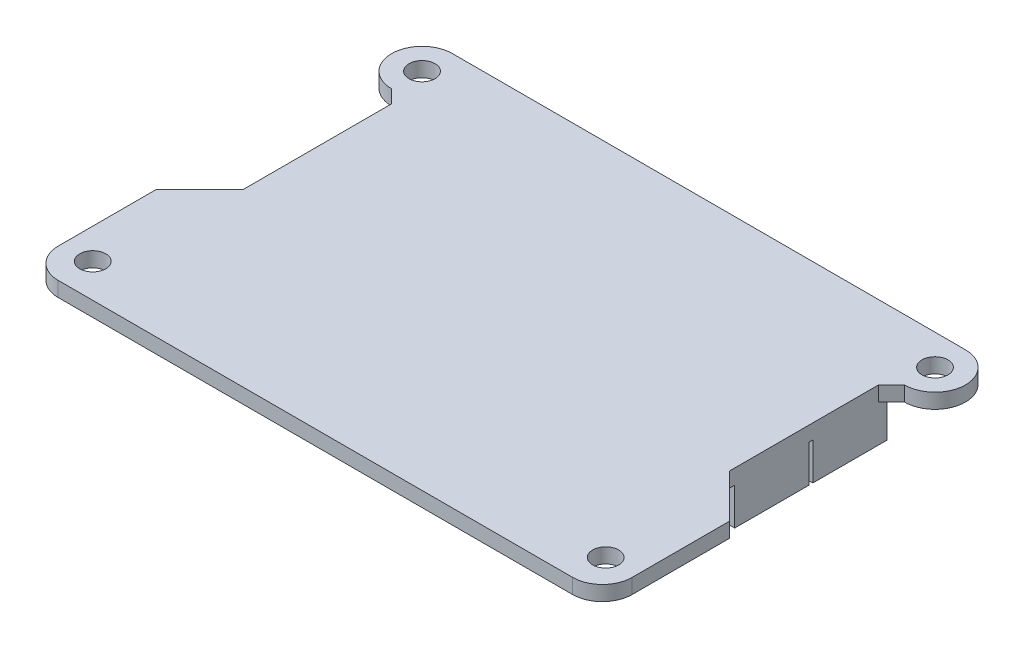
SolidWorks part; units mm, degrees
ref_plane "前视基准面" through (0, 0, 0) normal (0, 0, 1) x (1, 0, 0)
ref_plane "上视基准面" through (0, 0, 0) normal (0, 1, 0) x (1, 0, 0)
ref_plane "右视基准面" through (0, 0, 0) normal (1, 0, 0) x (0, 0, -1)
sketch "草图1" plane through (0, 0, 0) normal (0, 1, 0) x (1, 0, 0)
  line L0 (0, 0) -> (62.6522, 0) construction
  line L1 (0, 0) -> (0, 53.0134) construction
  line L2 (-34.475, 43.1409) -> (34.475, 43.1409)
  line L3 (34.475, 34.9509) -> (32.725, 33.2009)
  line L4 (32.725, 33.2009) -> (32.725, 13.2009)
  line L5 (32.725, 13.2009) -> (38.57, 7.3559)
  line L6 (38.57, 7.3559) -> (38.57, -9.7591)
  line L7 (38.57, -9.7591) -> (-38.57, -9.7591)
  line L8 (-38.57, 7.3559) -> (-38.57, -9.7591)
  line L9 (-32.725, 13.2009) -> (-38.57, 7.3559)
  line L10 (-32.725, 33.2009) -> (-32.725, 13.2009)
  line L11 (-34.475, 34.9509) -> (-32.725, 33.2009)
  arc A0 (34.475, 34.9509) -> (34.475, 43.1409) centre (34.475, 39.0459) ccw
  circle A1 centre (34.475, 39.0459) radius 1.75
  circle A2 centre (34.475, -5.2141) radius 1.75
  circle A3 centre (-34.475, -5.2141) radius 1.75
  circle A4 centre (-34.475, 39.0459) radius 1.75
  arc A5 (-34.475, 34.9509) -> (-34.475, 43.1409) centre (-34.475, 39.0459) cw
  point P23 (0, -9.7591)
  point P26 (0, 43.1409)
  dimension "D5" = 3.5
  dimension "D6" = 135
  dimension "D1" = 68.95
  dimension "D2" = 44.26
  dimension "D3" = 52.9
  dimension "D4" = 77.14
  dimension "D7" = 20
  dimension "D8" = 135
extrude "凸台-拉伸1" add sketch "草图1" along normal blind 2
fillet "圆角1" radius 4 2 edges at (-38.57, 1, 9.7591) (38.57, 1, 9.7591)
sketch "草图2" plane through (0, 0, 0) normal (0, -1, 0) x (1, 0, 0)
  line L0 (32.725, -13.2009) -> (32.725, -33.2009) construction
  line L1 (32.725, -34.3689) -> (27.725, -34.3689)
  line L2 (32.725, -34.3689) -> (32.725, -24.3689)
  line L3 (32.725, -24.3689) -> (27.725, -24.3689)
  line L4 (27.725, -34.3689) -> (27.725, -24.3689)
  line L5 (-27.725, -32.8455) -> (-32.725, -32.8455)
  line L6 (32.725, -23.8774) -> (27.725, -23.8774)
  line L7 (32.725, -23.8774) -> (32.725, -13.8774)
  line L8 (32.725, -13.8774) -> (27.725, -13.8774)
  line L9 (27.725, -23.8774) -> (27.725, -13.8774)
  line L10 (-27.725, -32.8455) -> (-27.725, -22.8455)
  line L11 (-27.725, -22.8455) -> (-32.725, -22.8455)
  line L12 (-32.725, -32.8455) -> (-32.725, -22.8455)
  line L13 (-32.725, -33.2009) -> (-32.725, -13.2009) construction
  dimension "D1" = 5
  dimension "D2" = 10
  dimension "D3" = 5
  dimension "D4" = 10
  dimension "D5" = 5
  dimension "D6" = 10
extrude "凸台-拉伸2" add sketch "草图2" along normal blind 5
sketch "草图4" plane through (0, -5, 0) normal (0, -1, 0) x (1, 0, 0)
  line L0 (31.631, -19.9862) -> (31.631, -17.9323)
  line L1 (31.631, -17.9323) -> (31.131, -17.9323)
  line L2 (31.131, -17.9323) -> (31.131, -18.6563)
  line L3 (31.131, -18.6563) -> (29.131, -18.6563)
  line L4 (29.131, -18.6563) -> (29.131, -17.9323)
  line L5 (29.131, -17.9323) -> (28.631, -17.9323)
  line L6 (28.631, -17.9323) -> (28.631, -19.9862)
  line L7 (28.631, -19.9862) -> (29.131, -19.9862)
  line L8 (29.131, -19.9862) -> (29.131, -19.152)
  line L9 (29.131, -19.152) -> (31.131, -19.152)
  line L10 (31.131, -19.152) -> (31.131, -19.9862)
  line L11 (31.131, -19.9862) -> (31.631, -19.9862)
  dimension "D1" = 3
  dimension "D2" = 0.5
  dimension "D3" = 0.5
  dimension "D4" = 0.4957
extrude "切除-拉伸1" cut sketch "草图4" against normal blind 0.2
sketch "草图5" plane through (0, 0, 0) normal (0, -1, 0) x (1, 0, 0)
  line L1 (-12.9615, -6.2539) -> (-31.138, -6.2539)
  line L2 (-12.9615, -6.2539) -> (-12.9615, 2.4297)
  line L3 (-12.9615, 2.4297) -> (-31.138, 2.4297)
  line L4 (-31.138, -6.2539) -> (-31.138, 2.4297)
  line L5 (-12.9615, -6.2539) -> (-31.138, 2.4297) construction
  line L6 (-12.9615, 2.4297) -> (-31.138, -6.2539) construction
  point P0 (-22.0497, -1.9121)
extrude "凸台-拉伸3" add sketch "草图5" along normal blind 5
